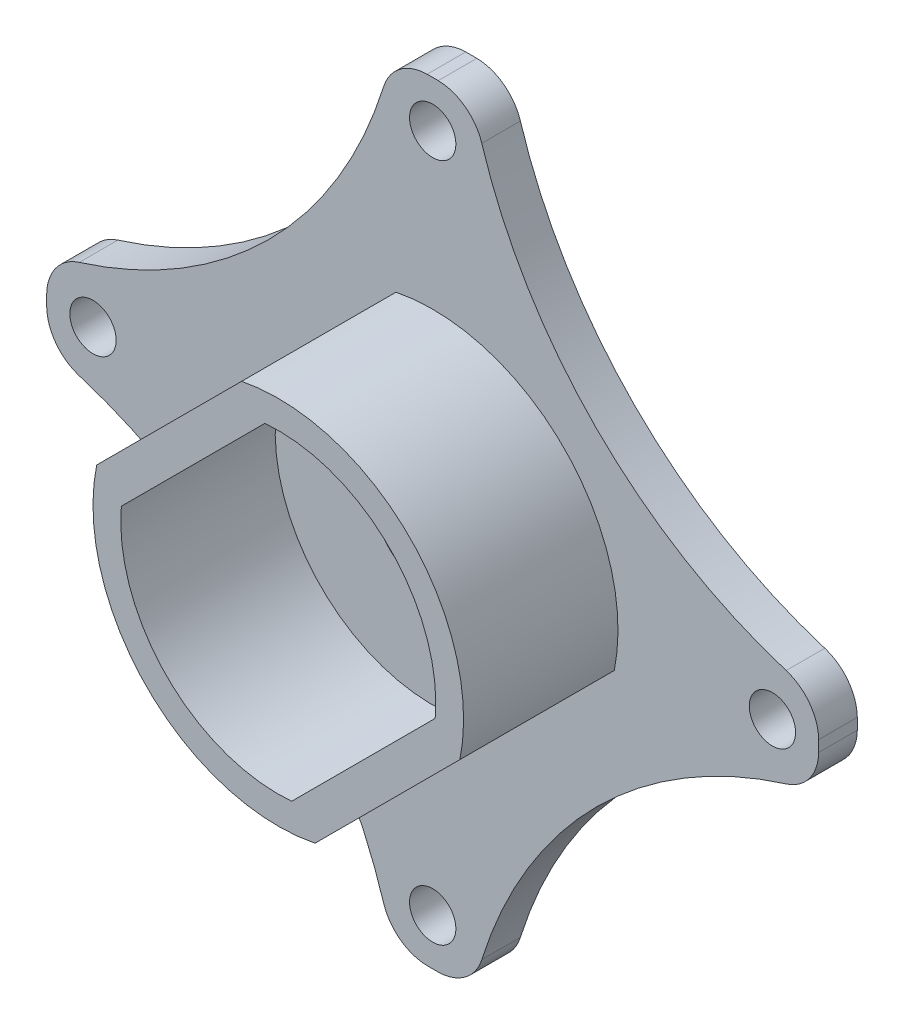
SolidWorks part; units mm, degrees
ref_plane "前视基准面" through (0, 0, 0) normal (0, 0, 1) x (1, 0, 0)
ref_plane "上视基准面" through (0, 0, 0) normal (0, 1, 0) x (1, 0, 0)
ref_plane "右视基准面" through (0, 0, 0) normal (1, 0, 0) x (0, 0, -1)
other "Configuration Table"
sketch "草图1" plane through (0, 0, 0) normal (0, 0, 1) x (1, 0, 0)
  line L0 (0, 0) -> (0, 22) construction
  line L1 (0, 0) -> (22, 0) construction
  circle A0 centre (0, 0) radius 22 construction
  circle A1 centre (0, 0) radius 16.5 construction
  circle A2 centre (0, 0) radius 25
  circle A3 centre (0, 22) radius 1.5
  circle A4 centre (22, 0) radius 1.5
  circle A5 centre (0, -22) radius 1.5
  circle A6 centre (-22, 0) radius 1.5
  dimension "D1" = 44
  dimension "D2" = 33
  dimension "D3" = 3
  dimension "D4" = 3
  dimension "D6" = 90
  dimension "D5" = 3
extrude "凸台-拉伸1" add sketch "草图1" along normal blind 2.5
sketch "草图3" plane through (0, 0, 0) normal (0, 0, -1) x (-1, 0, 0)
  line L0 (0, 0) -> (0, 22) construction
  circle A0 centre (0, 0) radius 10.5
  circle A1 centre (0, 0) radius 4
  circle A2 centre (0, 6.2) radius 1
  circle A3 centre (0, -6.2) radius 1
  dimension "D1" = 21
  dimension "D2" = 8
  dimension "D3" = 2
  dimension "D4" = 2
  dimension "D5" = 6.2
  dimension "D6" = 6.2
extrude "切除-拉伸2" cut sketch "草图3" against normal through all both and the other way through all contours A1
sketch "草图5" plane through (0, 0, 0) normal (0, 0, -1) x (-1, 0, 0)
  line L0 (-31.8198, 31.8198) -> (0, 0) construction
  line L1 (-22, 0) -> (0, 0) construction
  arc A0 (-24.8604, 2.6382) -> (-2.6382, 24.8604) centre (-31.8198, 31.8198) ccw
  circle A5 centre (0, 0) radius 25 construction
  arc A6 (2.6382, 24.8604) -> (24.8604, 2.6382) centre (31.8198, 31.8198) ccw
  circle A7 centre (0, 0) radius 25
  circle A8 centre (0, 0) radius 25
  arc A9 (24.8604, -2.6382) -> (2.6382, -24.8604) centre (31.8198, -31.8198) ccw
  arc A10 (-2.6382, -24.8604) -> (-24.8604, -2.6382) centre (-31.8198, -31.8198) ccw
  point P22 (0, 0)
  circle M3 centre (0, 0) radius 25
  dimension "D2" = 30
  dimension "D1" = 0
  dimension "D4" = 45
  dimension "D5" = 4
  dimension "D3" = 45
extrude "切除-拉伸5" cut sketch "草图5" against normal blind 10 contours A0 M3 | A8 A10 | A8 A9 | A6 M3
fillet "圆角2" radius 3 8 edges at (24.8604, 2.6382, 1.25) (2.6382, 24.8604, 1.25) (-2.6382, 24.8604, 1.25) (-24.8604, 2.6382, 1.25) (-24.8604, -2.6382, 1.25) (-2.6382, -24.8604, 1.25) (2.6382, -24.8604, 1.25) (24.8604, -2.6382, 1.25)
sketch "草图6" plane through (0, 0, 2.5) normal (0, 0, 1) x (1, 0, 0)
  line L0 (-10.163, 0.8679) -> (-0.8679, 10.163)
  line L1 (0, 0) -> (5.4954, 5.4954) construction
  line L2 (0.8679, -10.163) -> (10.163, -0.8679)
  line L3 (-11.7615, 2.3807) -> (-2.3807, 11.7615)
  line L4 (2.3807, -11.7615) -> (11.7615, -2.3807)
  line L5 (0, 0) -> (0, -2.6659) construction
  arc A0 (10.163, -0.8679) -> (-0.8679, 10.163) centre (0, 0) ccw
  arc A1 (-10.163, 0.8679) -> (0.8679, -10.163) centre (0, 0) ccw
  arc A2 (11.7615, -2.3807) -> (-2.3807, 11.7615) centre (0, 0) ccw
  arc A3 (-11.7615, 2.3807) -> (2.3807, -11.7615) centre (0, 0) ccw
  dimension "D1" = 20.4
  dimension "D3" = 24
  dimension "D2" = 15.6
  dimension "D4" = 20
  dimension "D5" = 135
extrude "凸台-拉伸2" add sketch "草图6" along normal blind 10
